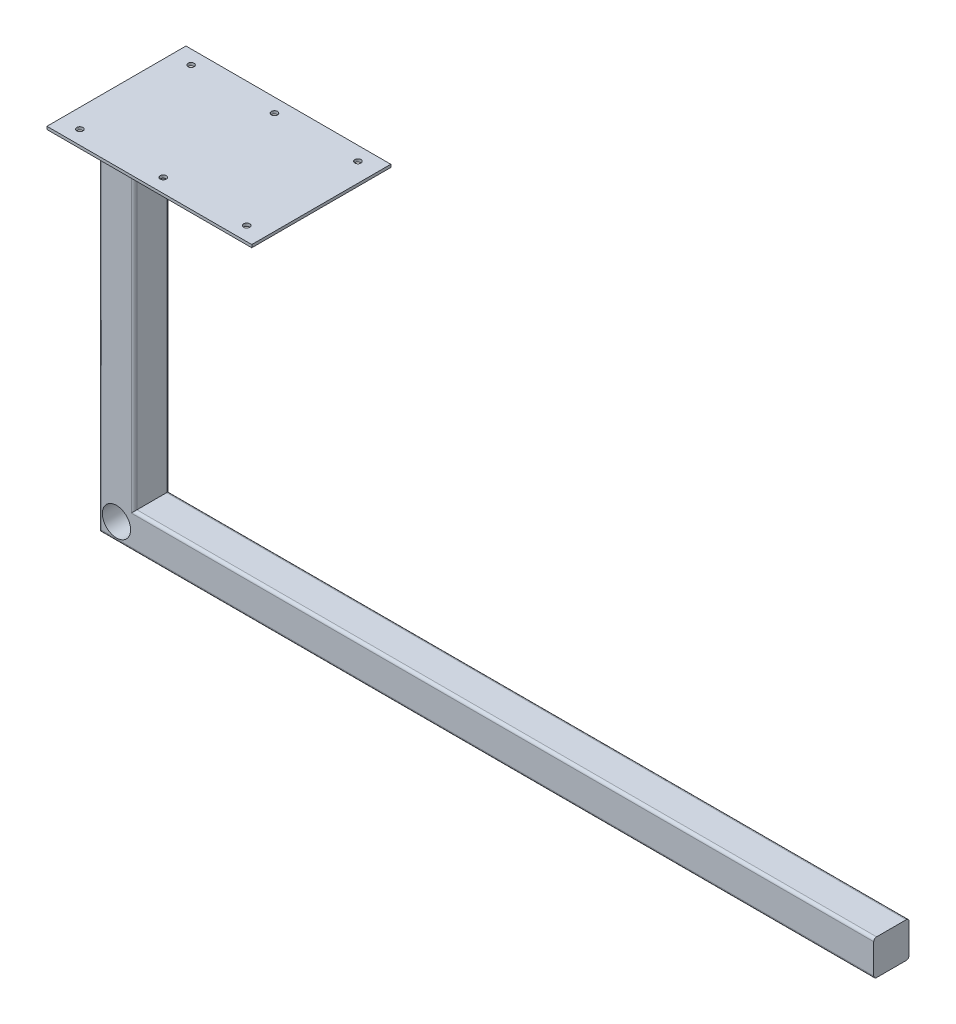
SolidWorks part; units mm, degrees
ref_plane "Front Plane" through (0, 0, 0) normal (0, 0, 1) x (1, 0, 0)
ref_plane "Top Plane" through (0, 0, 0) normal (0, 1, 0) x (1, 0, 0)
ref_plane "Right Plane" through (0, 0, 0) normal (1, 0, 0) x (0, 0, -1)
sketch "Sketch1" plane through (0, 0, 0) normal (0, 0, 1) x (1, 0, 0)
  line L0 (31.75, 31.75) -> (645.922, 31.75)
  line L1 (0, 336.55) -> (0, 0)
  line L2 (31.75, 336.55) -> (31.75, 31.75)
  line L3 (0, 0) -> (645.922, 0)
  line L4 (31.75, 336.55) -> (0, 336.55)
  line L6 (0, 0) -> (31.75, 31.75) construction
  line L7 (0, 0) -> (0, 614.172) construction
  line L9 (645.922, 31.75) -> (696.722, 31.75)
  line L11 (645.922, 0) -> (696.722, 0)
  line L12 (696.722, 31.75) -> (696.722, 0)
  circle A0 centre (15.875, 15.875) radius 12.7
  point P8 (0, 0)
  dimension "D4" = 25.4
  dimension "D2" = 304.8
  dimension "D3" = 50.8
  dimension "D5" = 15.875
  dimension "D6" = 15.875
  dimension "D7" = 277.622
  dimension "D1" = 31.75
extrude "Boss-Extrude1" add sketch "Sketch1" along normal blind 31.75 contours A0 L6 | L6 A0 | L2 L0 L9 L12 L11 L3 L1 L4
fillet "Fillet1" radius 2.54 8 edges at (348.361, 0, 0) (348.361, 0, 31.75) (364.236, 31.75, 31.75) (364.236, 31.75, 0) (0, 168.275, 0) (31.75, 184.15, 0) (0, 168.275, 31.75) (31.75, 184.15, 31.75)
sketch "Sketch3" plane through (0, 336.55, 0) normal (0, 1, 0) x (1, 0, 0)
  line L1 (0, 46.625) -> (184.15, 46.625)
  line L2 (0, 46.625) -> (0, -78.375)
  line L3 (0, -78.375) -> (184.15, -78.375)
  line L4 (184.15, 46.625) -> (184.15, -78.375)
  line L5 (22.0306, 46.625) -> (22.0306, 0) construction
  line L6 (29.21, 0) -> (2.54, 0) construction
  line L7 (22.0306, -78.375) -> (22.0306, -31.75) construction
  line L8 (29.21, -31.75) -> (2.54, -31.75) construction
  line L9 (0, -29.21) -> (0, -2.54) construction
  dimension "D1" = 125
  dimension "D2" = 184.15
extrude "Boss-Extrude2" add sketch "Sketch3" along normal blind 2.54
hole_wizard "M5 Clearance Hole1" positions "Sketch10" profile "Sketch8" hole size "M5" standard "ANSI Metric" end condition up to next
sketch "Sketch10" plane through (0, 339.09, 0) normal (0, 1, 0) x (1, 0, 0)
  line L1 (17.075, -65.875) -> (167.075, -65.875)
  line L2 (17.075, -65.875) -> (17.075, 34.125)
  line L3 (17.075, 34.125) -> (167.075, 34.125)
  line L4 (167.075, -65.875) -> (167.075, 34.125)
  line L5 (17.075, -65.875) -> (167.075, 34.125) construction
  line L6 (17.075, 34.125) -> (167.075, -65.875) construction
  line L9 (17.075, 21.8561) -> (0, 21.8561) construction
  line L10 (0, 46.625) -> (0, -78.375) construction
  line L12 (167.075, 21.8561) -> (184.15, 21.8561) construction
  line L13 (184.15, -78.375) -> (184.15, 46.625) construction
  line L15 (95.8564, 34.125) -> (95.8564, 46.625) construction
  line L16 (184.15, 46.625) -> (0, 46.625) construction
  line L18 (95.8564, -65.875) -> (95.8564, -78.375) construction
  line L19 (0, -78.375) -> (184.15, -78.375) construction
  point P3 (167.075, 34.125)
  point P138 (17.075, -65.875)
  point P139 (17.075, 34.125)
  point P140 (167.075, -65.875)
  point P179 (92.075, 34.125)
  point P181 (92.075, -65.875)
  dimension "D1" = 100
  dimension "D2" = 150
sketch "Sketch8" plane through (167.075, 339.09, -34.125) normal (1, 0, 0) x (0, 0, 1)
  line L0 (0, 0) -> (0, 2.54)
  line L1 (0, 2.54) -> (2.775, 2.54)
  line L2 (2.75, 2.515) -> (2.75, 0)
  line L5 (2.75, 0) -> (0, 0)
  line L7 (2.775, 2.54) -> (2.75, 2.515)
  line L8 (-2.775, 2.54) -> (-2.75, 2.515) construction
  line L11 (0, -6.35) -> (0, 107.95) construction
  dimension "Thru Hole Dia." = 5.5
  dimension "Thru Hole Depth" = 2.54
  dimension "Far C'Sink Dia." = 5.55
  dimension "Far C'Sink Angle" = 90
